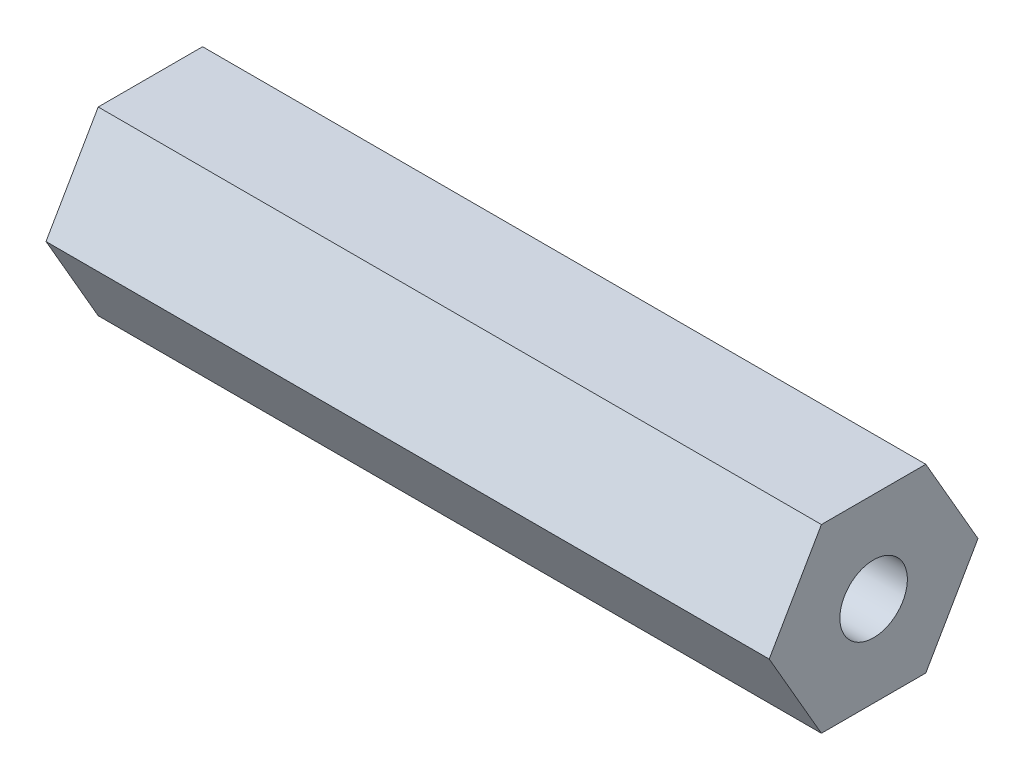
SolidWorks part; units mm, degrees
ref_plane "Front Plane" through (0, 0, 0) normal (0, 0, 1) x (1, 0, 0)
ref_plane "Top Plane" through (0, 0, 0) normal (0, 1, 0) x (1, 0, 0)
ref_plane "Right Plane" through (0, 0, 0) normal (1, 0, 0) x (0, 0, -1)
sketch "Sketch1" plane through (0, 0, 0) normal (1, 0, 0) x (0, 0, -1)
  line L0 (0, 0) -> (0, 2.3813) construction
  line L1 (-1.3748, -2.3812) -> (1.3748, -2.3812)
  line L2 (1.3748, -2.3812) -> (2.7496, 0)
  line L3 (2.7496, 0) -> (1.3748, 2.3813)
  line L4 (1.3748, 2.3813) -> (-1.3748, 2.3813)
  line L5 (-1.3748, 2.3813) -> (-2.7496, 0)
  line L6 (-2.7496, 0) -> (-1.3748, -2.3812)
  circle A0 centre (0, 0) radius 2.3812 construction
  dimension "D1" = 4.7625
extrude "Boss-Extrude1" add sketch "Sketch1" along normal blind 19.05
hole_wizard "#2-56 Tapped Hole1" positions "Sketch3" profile "Sketch2" tap size "#2-56" standard "ANSI Inch" end condition through all
sketch "Sketch3" plane through (0, 0, 0) normal (-1, 0, 0) x (0, 0, 1)
  point P0 (0, 0)
sketch "Sketch2" plane through (0, 0, 0) normal (0, 1, 0) x (0, 0, 1)
  line L0 (0, 0) -> (0, 19.05)
  line L1 (0, 19.05) -> (0.889, 19.05)
  line L2 (0.889, 19.05) -> (0.889, 0)
  line L5 (0.889, 0) -> (0, 0)
  line L11 (0, -6.35) -> (0, 107.95) construction
  dimension "Thru Tap Drill Dia." = 1.778
  dimension "Thru Tap Drill Depth" = 19.05
cosmetic thread "Hole Thread1" parameters "D2"=2.1844
